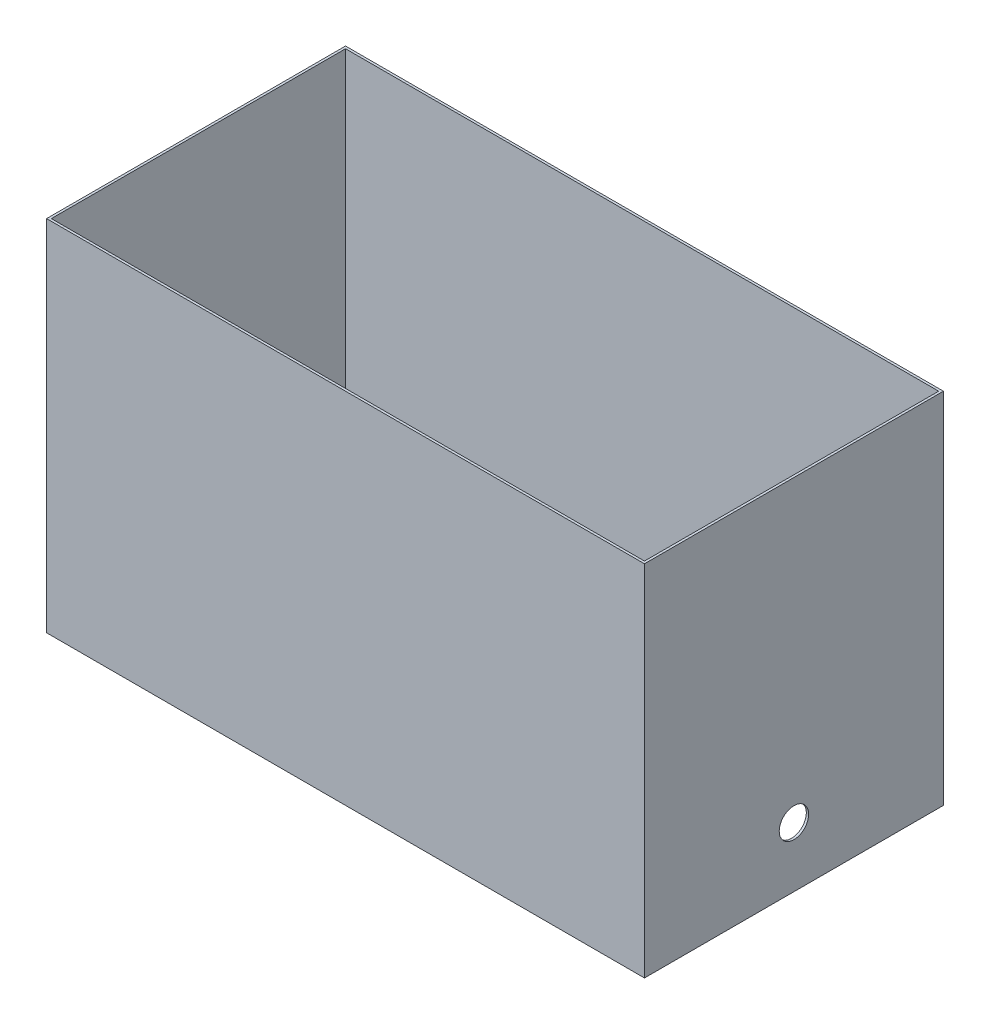
SolidWorks part; units mm, degrees
material "Galvanized Steel"
ref_plane "Front Plane" through (0, 0, 0) normal (0, 0, 1) x (1, 0, 0)
ref_plane "Top Plane" through (0, 0, 0) normal (0, 1, 0) x (1, 0, 0)
ref_plane "Right Plane" through (0, 0, 0) normal (1, 0, 0) x (0, 0, -1)
sketch "Sketch1" plane through (0, 0, 0) normal (0, 1, 0) x (1, 0, 0)
  line L0 (-252, 125) -> (252, 125)
  line L1 (-254, -127) -> (254, -127)
  line L2 (-254, -127) -> (-254, 127)
  line L3 (-254, 127) -> (254, 127)
  line L4 (254, -127) -> (254, 127)
  line L5 (-254, -127) -> (254, 127) construction
  line L6 (-254, 127) -> (254, -127) construction
  line L7 (252, -125) -> (252, 125)
  line L8 (-252, -125) -> (252, -125)
  line L9 (-252, -125) -> (-252, 125)
  point P0 (0, 0)
  dimension "D1" = 254
  dimension "D2" = 508
  dimension "D3" = 2
extrude "Boss-Extrude1" add sketch "Sketch1" along normal blind 304.8
sketch "Sketch2" plane through (-254, 0, 0) normal (-1, 0, 0) x (0, 0, 1)
  line L0 (0, 50.8) -> (0, 0) construction
  line L1 (-127, 0) -> (127, 0) construction
  circle A0 centre (0, 50.8) radius 12.5
  dimension "D1" = 50.8
  dimension "D2" = 25
extrude "Cut-Extrude1" cut sketch "Sketch2" against normal through all
